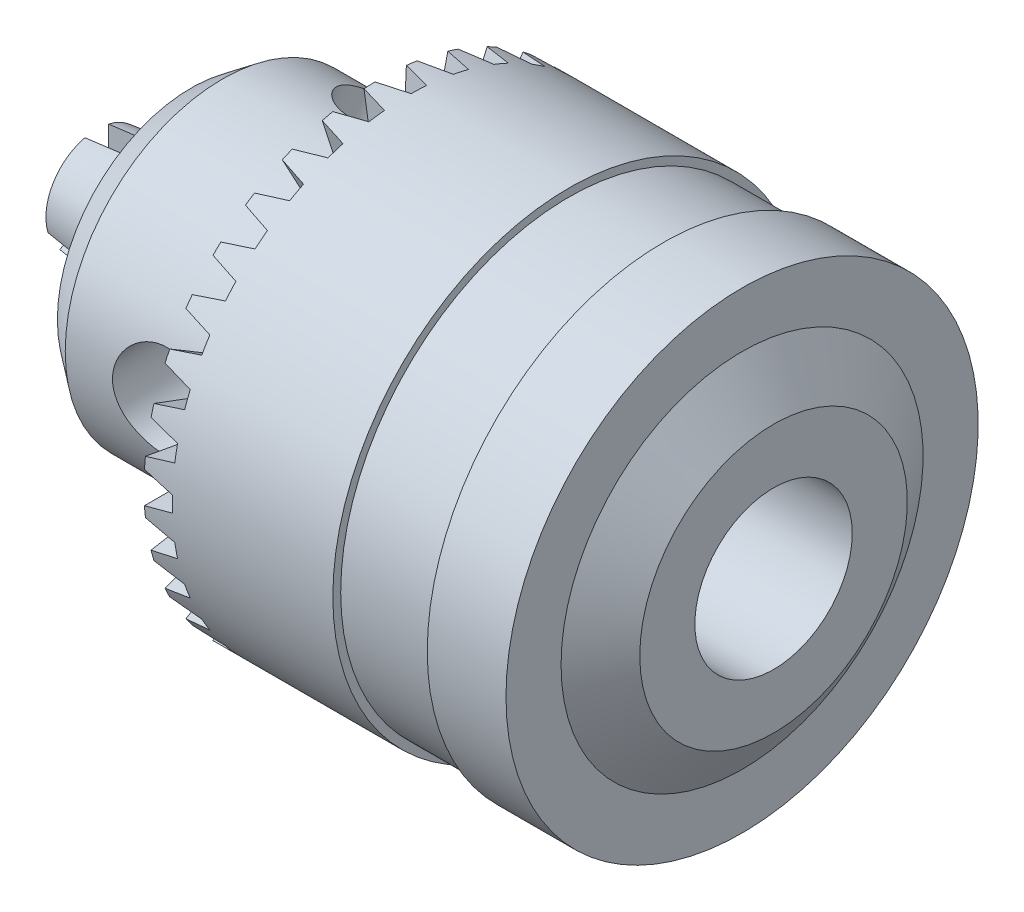
SolidWorks part; units mm, degrees
ref_plane "Ön Düzlem" through (0, 0, 0) normal (0, 0, 1) x (1, 0, 0)
ref_plane "Üst Düzlem" through (0, 0, 0) normal (0, 1, 0) x (1, 0, 0)
ref_plane "Sağ Düzlem" through (0, 0, 0) normal (1, 0, 0) x (0, 0, -1)
sketch "Sketch1" plane through (0, 0, 0) normal (0, 0, 1) x (1, 0, 0)
  line L0 (-18.5, 0) -> (18.5, 0)
  line L1 (18.5, 0) -> (18.5, 8.5)
  line L3 (16.5, 15) -> (11.5, 15)
  line L4 (11.5, 15) -> (11.5, 14.5)
  line L5 (11.5, 14.5) -> (5.5, 14.5)
  line L6 (5.5, 14.5) -> (5.5, 15)
  line L7 (5.5, 15) -> (-6.5, 15)
  line L8 (-6.5, 15) -> (-6.5, 10)
  line L9 (-6.5, 10) -> (-16.5, 10)
  line L10 (-16.5, 10) -> (-18.5, 8.5)
  line L11 (-18.5, 8.5) -> (-18.5, 0)
  line L12 (16.5, 15) -> (16.5, 11.5)
  line L13 (16.5, 11.5) -> (18.5, 8.5)
  point P0 (-14.8303, 10)
  dimension "D1" = 15
  dimension "D2" = 14.5
  dimension "D3" = 8.5
  dimension "D4" = 11.5
  dimension "D5" = 2
  dimension "D6" = 5
  dimension "D7" = 8.5
  dimension "D8" = 5
  dimension "D9" = 6
  dimension "D10" = 12
  dimension "D11" = 10
  dimension "D12" = 2
revolve "Revolve1" add sketch "Sketch1" angle 360 about L0
sketch "Sketch2" plane through (18.5, 0, 0) normal (1, 0, 0) x (0, 0, -1)
  circle A0 centre (0, 0) radius 5
  dimension "D1" = 10
extrude "Cut-Extrude1" cut sketch "Sketch2" against normal blind 16.7
sketch "Sketch3" plane through (-18.5, 0, 0) normal (-1, 0, 0) x (0, 0, 1)
  circle A4 centre (0, 0) radius 4
  dimension "D1" = 8
extrude "Cut-Extrude2" cut sketch "Sketch3" against normal up to next
ref_plane "Plane1" through (0, 0, 10) normal (0, 0, 1) x (1, 0, 0)
sketch "Sketch4" plane through (0, 0, 10) normal (0, 0, 1) x (1, 0, 0)
  line L0 (-18.5, 8.5) -> (-18.5, -8.5) construction
  circle A0 centre (-10.5, 0) radius 3
  point P4 (-8.5, 0)
  dimension "D1" = 6
  dimension "D2" = 8
extrude "Cut-Extrude3" cut sketch "Sketch4" against normal blind 4.65
pattern_circular "CirPattern1" count 3 over 360 about axis through (0, 0, 0) along (1, 0, 0) of "Cut-Extrude3"
sketch "Sketch5" plane through (0, 0, 10) normal (0, 0, 1) x (1, 0, 0)
  line L0 (-6.5, 1) -> (-4.7, 0.5)
  line L1 (-6.5, 15) -> (-6.5, -15) construction
  line L2 (-4.7, 0.5) -> (-4.7, -0.5)
  line L3 (-4.7, -0.5) -> (-6.5, -1)
  line L4 (-6.5, -1) -> (-6.5, 1)
  dimension "D1" = 1.8
  dimension "D2" = 1
  dimension "D3" = 2
  dimension "D4" = 1
  dimension "D5" = 0.5
extrude "Cut-Extrude4" cut sketch "Sketch5" along normal up to next
pattern_circular "CirPattern2" count 35 over 360 about axis through (0, 0, 0) along (1, 0, 0) of "Cut-Extrude4"
sketch "Sketch6" plane through (-18.5, 0, 0) normal (-1, 0, 0) x (0, 0, 1)
  line L3 (0.75, 3.9774) -> (0.75, 0.433)
  line L4 (0.75, 0.433) -> (3.8195, -1.3392)
  line L5 (-0.75, 3.9774) -> (-0.75, 0.433)
  line L6 (-0.75, 0.433) -> (-3.8195, -1.3392)
  line L7 (-5.1354, 0) -> (-1.5, 0) construction
  line L8 (0, -0.866) -> (-3.0695, -2.6382)
  line L9 (0, -0.866) -> (3.0695, -2.6382)
  line L10 (1.5, 0) -> (6.6582, 0) construction
  arc A1 (-0.75, 3.9774) -> (-3.8195, -1.3392) centre (0, 0) ccw
  arc A2 (3.8195, -1.3392) -> (0.75, 3.9774) centre (0, 0) ccw
  arc A3 (-3.0695, -2.6382) -> (3.0695, -2.6382) centre (0, 0) ccw
  point P2 (0, -0.8536)
extrude "Boss-Extrude1" add sketch "Sketch6" along normal blind 6
ref_plane "Plane2" through (0, 0, 0) normal (0, 0.866, -0.5) x (1, 0, 0)
sketch "Sketch12" plane through (0, 0, 0) normal (0, 0.866, -0.5) x (1, 0, 0)
  line L0 (-18.5, 4.3774) -> (-24.5, 4.3774)
  line L1 (-18.5, 8.5) -> (-18.5, -8.5) construction
  line L2 (-24.5, 4.3774) -> (-24.5, 3.2274)
  line L3 (-24.5, 3.9774) -> (-24.5, -1.3392) construction
  line L5 (-24.5, 3.2274) -> (-18.5, 3.9774)
  line L6 (-18.5, 3.9774) -> (-18.5, -1.3392) construction
  line L7 (-18.5, 3.9774) -> (-18.5, 4.3774)
  line L8 (-10.3744, 0) -> (-28.5701, 0) construction
  dimension "D1" = 0.75
  dimension "D2" = 0.4
revolve "Cut-Revolve3" cut sketch "Sketch12" angle 360 about L8
sketch "Sketch14" plane through (0, 0, 0) normal (0, 0.866, -0.5) x (1, 0, 0)
  line L0 (-18.5, 0.433) -> (-13.4547, 4)
  line L1 (1.8, 4) -> (-18.5, 4) construction
  line L2 (-18.5, 0.433) -> (-18.5, 4)
  line L3 (-18.5, 4) -> (-13.4547, 4)
  line L4 (-10.5, 0) -> (-27.1183, 0) construction
revolve "Revolve2" add sketch "Sketch14" angle 360 about L4
sketch "Sketch15" plane through (-18.5, 0, 0) normal (-1, 0, 0) x (0, 0, 1)
  line L0 (0.75, 3.906) -> (0.75, 0.433) construction
  line L1 (0.75, 0.433) -> (3.7577, -1.3035) construction
  line L2 (3.0077, -2.6025) -> (0, -0.866) construction
  line L3 (0, -0.866) -> (-3.0077, -2.6025) construction
  line L4 (-3.7577, -1.3035) -> (-0.75, 0.433) construction
  line L5 (-0.75, 0.433) -> (-0.75, 3.906) construction
  line L6 (0.75, 3.906) -> (0.75, 0.433)
  line L7 (0.75, 0.433) -> (3.7577, -1.3035)
  line L8 (3.0077, -2.6025) -> (0, -0.866)
  line L9 (0, -0.866) -> (-3.0077, -2.6025)
  line L10 (-3.7577, -1.3035) -> (-0.75, 0.433)
  line L11 (-0.75, 0.433) -> (-0.75, 3.906)
  line L12 (-0.75, 3.906) -> (0.75, 3.906)
  line L13 (3.7577, -1.3035) -> (3.0077, -2.6025)
  line L14 (-3.7577, -1.3035) -> (-3.0077, -2.6025)
extrude "Cut-Extrude5" cut sketch "Sketch15" against normal up to next
